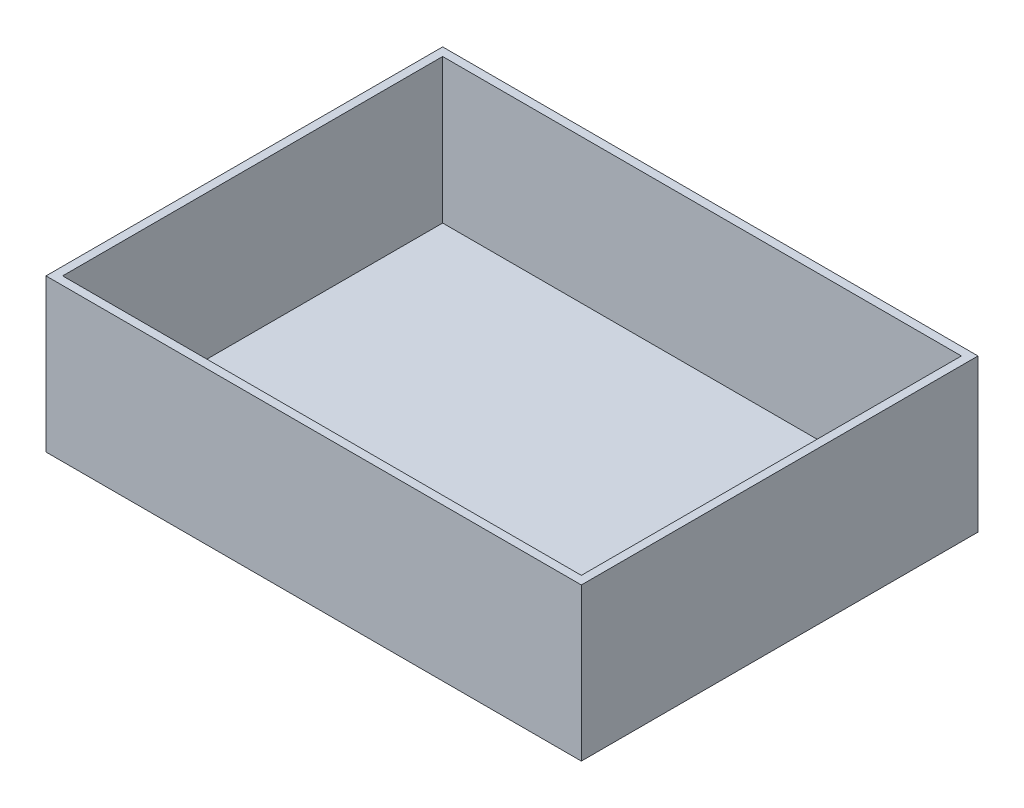
SolidWorks part; units mm, degrees
ref_plane "Front Plane" through (0, 0, 0) normal (0, 0, 1) x (1, 0, 0)
ref_plane "Top Plane" through (0, 0, 0) normal (0, 1, 0) x (1, 0, 0)
ref_plane "Right Plane" through (0, 0, 0) normal (1, 0, 0) x (0, 0, -1)
sketch "Sketch1" plane through (0, 0, 0) normal (0, 1, 0) x (1, 0, 0)
  line L1 (-96.5, -71.5) -> (96.5, -71.5)
  line L2 (-96.5, -71.5) -> (-96.5, 71.5)
  line L3 (-96.5, 71.5) -> (96.5, 71.5)
  line L4 (96.5, -71.5) -> (96.5, 71.5)
  line L5 (-96.5, -71.5) -> (96.5, 71.5) construction
  line L6 (-96.5, 71.5) -> (96.5, -71.5) construction
  point P0 (0, 0)
  dimension "D1" = 193
  dimension "D2" = 143
extrude "Boss-Extrude1" add sketch "Sketch1" along normal blind 55
shell "Shell1" thickness 3
